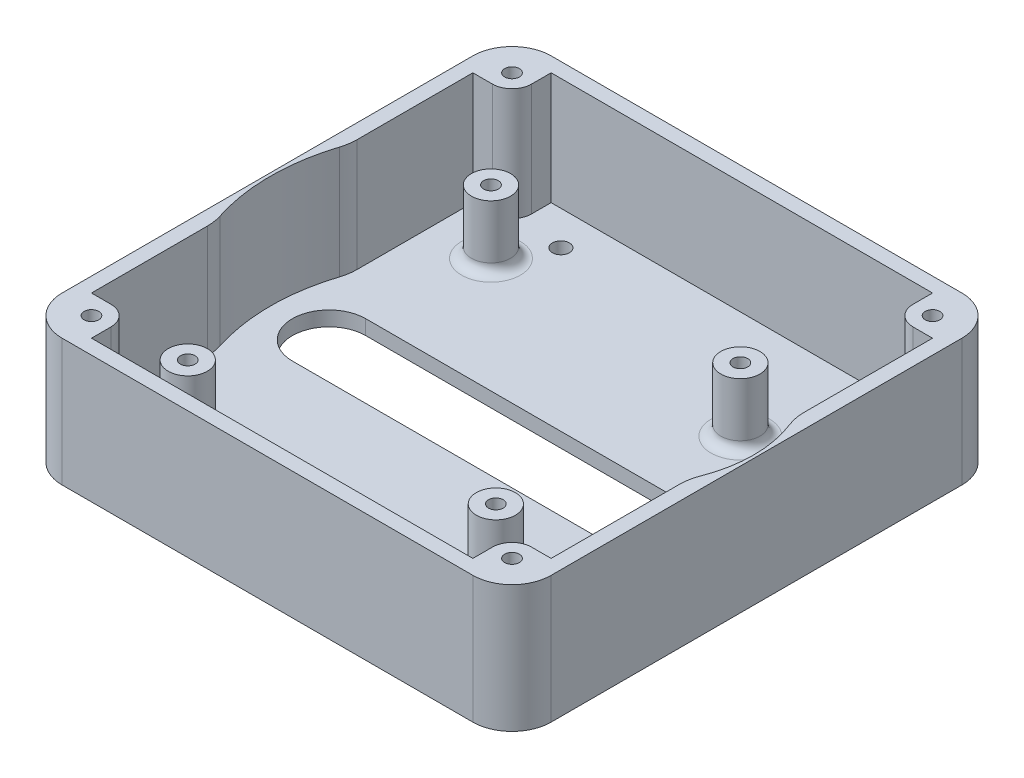
SolidWorks part; units mm, degrees
ref_plane "Спереди" through (0, 0, 0) normal (0, 0, 1) x (1, 0, 0)
ref_plane "Сверху" through (0, 0, 0) normal (0, 1, 0) x (1, 0, 0)
ref_plane "Справа" through (0, 0, 0) normal (1, 0, 0) x (0, 0, -1)
sketch "Эскиз1" plane through (0, 0, 0) normal (0, 1, 0) x (1, 0, 0)
  line L0 (0, 50) -> (100, 50) construction
  line L17 (0, 0) -> (100, 0)
  line L18 (0, 0) -> (0, 100)
  line L19 (0, 100) -> (100, 100)
  line L20 (100, 0) -> (100, 100)
  line L21 (50, 100) -> (50, 0) construction
  circle A0 centre (14.7, 81) radius 1.5
  circle A1 centre (71.7, 75) radius 1.5
  circle A2 centre (71.7, 25) radius 1.5
  circle A3 centre (14.7, 19) radius 1.5
  circle A5 centre (7, 93) radius 1.5
  circle A6 centre (93, 93) radius 1.5
  circle A7 centre (93, 7) radius 1.5
  circle A8 centre (7, 7) radius 1.5
  dimension "D3" = 3
  dimension "D8" = 3
  dimension "D1" = 100
  dimension "D2" = 100
  dimension "D4" = 62
  dimension "D5" = 50
  dimension "D6" = 57
  dimension "D7" = 28.3
  dimension "D9" = 7
  dimension "D10" = 7
extrude "Бобышка-Вытянуть1" add sketch "Эскиз1" along normal blind 3
sketch "Эскиз4" plane through (0, 3, 0) normal (0, 1, 0) x (1, 0, 0)
  line L0 (97, 97) -> (3, 97)
  line L1 (3, 97) -> (3, 65.3049)
  line L2 (3, 3) -> (97, 3)
  line L3 (97, 3) -> (97, 37.2627)
  line L4 (0, 100) -> (0, 0)
  line L5 (0, 0) -> (100, 0)
  line L6 (100, 0) -> (100, 100)
  line L7 (100, 100) -> (0, 100)
  line L8 (0, 100) -> (0, 0)
  line L9 (0, 0) -> (100, 0)
  line L10 (100, 0) -> (100, 100)
  line L11 (100, 100) -> (0, 100)
  line L12 (0, 50) -> (100, 50) construction
  line L13 (3, 34.6951) -> (3, 3)
  line L14 (3, 97) -> (3, 3) construction
  line L15 (97, 62.7373) -> (97, 97)
  line L16 (97, 3) -> (97, 97) construction
  arc A0 (2.52, 62.2439) -> (2.52, 37.7561) centre (40.6, 50) ccw
  arc A1 (97.6857, 40.9019) -> (97.6857, 59.0981) centre (74.4, 50) ccw
  arc A2 (97.6857, 59.0981) -> (97, 62.7373) centre (107, 62.7373) cw
  arc A3 (97.6857, 40.9019) -> (97, 37.2627) centre (107, 37.2627) ccw
  arc A4 (2.52, 37.7561) -> (3, 34.6951) centre (-7, 34.6951) cw
  arc A5 (2.52, 62.2439) -> (3, 65.3049) centre (-7, 65.3049) ccw
  point P12 (0.6, 50)
  point P16 (99.4, 50)
  point P20 (97, 60.6883)
  point P25 (3, 36.353)
  dimension "D4" = 80
  dimension "D6" = 50
  dimension "D7" = 10
  dimension "D3" = 0.6
  dimension "D5" = 0.6
  dimension "D1" = 0
  dimension "D2" = 3
extrude "Бобышка-Вытянуть4" add sketch "Эскиз4" along normal blind 23
sketch "Эскиз5" plane through (0, 3, 0) normal (0, 1, 0) x (1, 0, 0)
  circle A0 centre (14.7, 81) radius 4
  circle A1 centre (14.7, 81) radius 1.5 construction
  circle A2 centre (14.7, 81) radius 1.5
  circle A3 centre (14.7, 19) radius 1.5 construction
  circle A4 centre (71.7, 25) radius 1.5 construction
  circle A5 centre (71.7, 75) radius 1.5 construction
  circle A6 centre (14.7, 19) radius 1.5
  circle A7 centre (71.7, 25) radius 1.5
  circle A8 centre (71.7, 75) radius 1.5
  circle A9 centre (71.7, 75) radius 4
  circle A10 centre (71.7, 25) radius 4
  circle A11 centre (14.7, 19) radius 4
  dimension "D1" = 8
extrude "Бобышка-Вытянуть5" add sketch "Эскиз5" along normal blind 13
fillet "Скругление2" radius 2 4 edges at (14.7, 3, -23) (71.7, 3, -29) (71.7, 3, -79) (14.7, 3, -85)
fillet "Скругление3" radius 8 4 edges at (100, 13, -100) (100, 13, 0) (0, 13, 0) (0, 13, -100)
sketch "Эскиз7" plane through (0, 3, 0) normal (0, 1, 0) x (1, 0, 0)
  line L0 (3, 97) -> (3, 65.3049) construction
  line L2 (97, 97) -> (3, 97) construction
  line L6 (50, 97) -> (50, 3) construction
  line L7 (3, 3) -> (97, 3) construction
  line L8 (0, 50) -> (100, 50) construction
  line L9 (0, 92) -> (0, 8) construction
  line L10 (100, 8) -> (100, 92) construction
  line L15 (3, 89) -> (3, 97)
  line L16 (3, 97) -> (11, 97)
  line L17 (7, 89) -> (3, 89)
  line L18 (3, 97) -> (3, 65.3049) construction
  line L19 (11, 93) -> (11, 97)
  line L20 (97, 97) -> (3, 97) construction
  line L21 (89, 93) -> (89, 97)
  line L22 (93, 89) -> (97, 89)
  line L23 (97, 97) -> (89, 97)
  line L24 (97, 89) -> (97, 97)
  line L25 (97, 11) -> (97, 3)
  line L26 (97, 3) -> (89, 3)
  line L27 (93, 11) -> (97, 11)
  line L28 (89, 7) -> (89, 3)
  line L29 (11, 7) -> (11, 3)
  line L30 (7, 11) -> (3, 11)
  line L31 (3, 3) -> (11, 3)
  line L32 (3, 11) -> (3, 3)
  arc A0 (7, 89) -> (11, 93) centre (7, 93) ccw
  circle A17 centre (7, 93) radius 1.5 construction
  circle A18 centre (7, 93) radius 1.5
  circle A19 centre (93, 93) radius 1.5
  arc A20 (93, 89) -> (89, 93) centre (93, 93) cw
  arc A21 (93, 11) -> (89, 7) centre (93, 7) ccw
  circle A22 centre (93, 7) radius 1.5
  circle A23 centre (7, 7) radius 1.5
  arc A24 (7, 11) -> (11, 7) centre (7, 7) cw
extrude "Бобышка-Вытянуть6" add sketch "Эскиз7" along normal up to surface (23 mm away) up to face at (50, 26, -50)
sketch "Эскиз8" plane through (0, 3, 0) normal (0, 1, 0) x (1, 0, 0)
  line L0 (0, 50) -> (100, 50) construction
  line L1 (0, 92) -> (0, 8) construction
  line L2 (100, 8) -> (100, 92) construction
  line L3 (50, 100) -> (50, 0) construction
  line L4 (92, 100) -> (8, 100) construction
  line L5 (8, 0) -> (92, 0) construction
  line L6 (12.5921, 50) -> (87.5921, 50) construction
  line L7 (12.5921, 57.5) -> (87.5921, 57.5)
  line L8 (12.5921, 42.5) -> (87.5921, 42.5)
  arc A0 (12.5921, 57.5) -> (12.5921, 42.5) centre (12.5921, 50) ccw
  arc A1 (87.5921, 42.5) -> (87.5921, 57.5) centre (87.5921, 50) ccw
  circle A2 centre (20, 90) radius 1.75
  circle A3 centre (80, 90) radius 1.75
  circle A4 centre (80, 10) radius 1.75
  circle A5 centre (20, 10) radius 1.75
  circle A6 centre (89.9004, 61.5084) radius 2
  circle A7 centre (80, 61.5084) radius 2
  point P14 (50.0921, 50)
  dimension "D3" = 3.5
  dimension "D6" = 4
  dimension "D1" = 15
  dimension "D2" = 75
  dimension "D4" = 60
  dimension "D5" = 80
extrude "Вырез-Вытянуть2" cut sketch "Эскиз8" against normal up to surface (3 mm away) up to face at (93, 0, -5.5)
